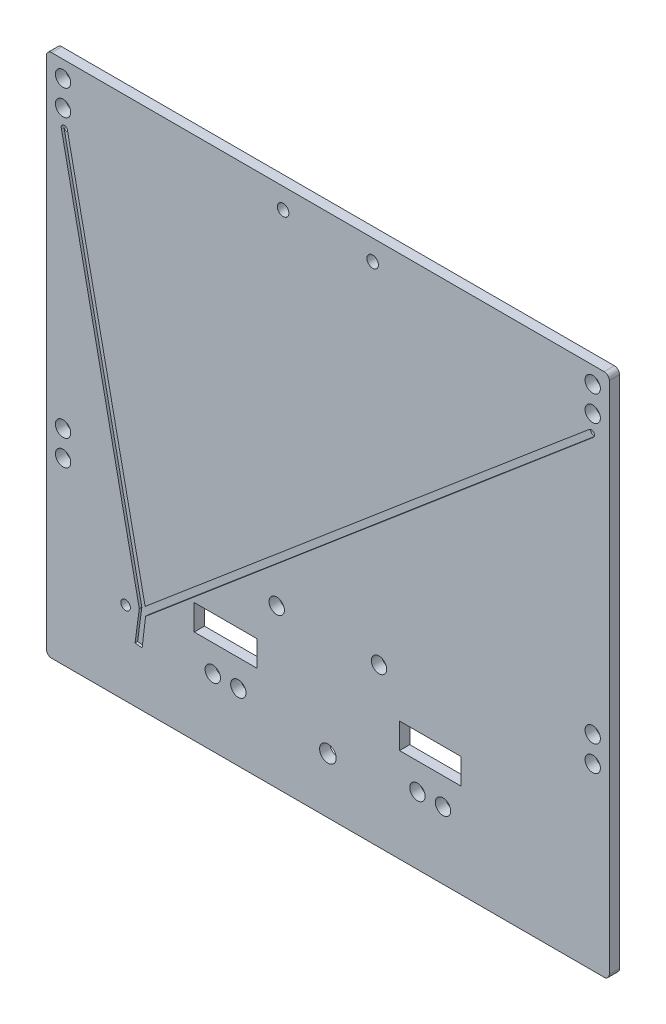
SolidWorks part; units mm, degrees
ref_plane "Front Plane" through (0, 0, 0) normal (0, 0, 1) x (1, 0, 0)
ref_plane "Top Plane" through (0, 0, 0) normal (0, 1, 0) x (1, 0, 0)
ref_plane "Right Plane" through (0, 0, 0) normal (1, 0, 0) x (0, 0, -1)
sketch "Sketch1" plane through (0, 0, 384.6201) normal (0, 0, -1) x (-1, 0, 0)
  line L5 (7.2108, -530.2989) -> (55.2108, -530.2989)
  line L6 (7.2108, -530.2989) -> (7.2108, -510.2989)
  line L7 (7.2108, -510.2989) -> (55.2108, -510.2989)
  line L8 (-108.7892, -197.7989) -> (-108.7892, -599.7989)
  line L9 (-104.7892, -603.7989) -> (327.2108, -603.7989)
  line L10 (331.2108, -599.7989) -> (331.2108, -197.7989)
  line L11 (327.2108, -193.7989) -> (-104.7892, -193.7989)
  line L12 (-108.7892, -197.7989) -> (-108.7892, -599.7989)
  line L13 (-104.7892, -603.7989) -> (327.2108, -603.7989)
  line L14 (331.2108, -599.7989) -> (331.2108, -197.7989)
  line L15 (327.2108, -193.7989) -> (-104.7892, -193.7989)
  line L16 (55.2108, -530.2989) -> (55.2108, -510.2989)
  line L17 (7.2108, -530.2989) -> (55.2108, -510.2989) construction
  line L18 (7.2108, -510.2989) -> (55.2108, -530.2989) construction
  line L19 (166.7108, -530.2989) -> (215.7108, -530.2989)
  line L20 (166.7108, -530.2989) -> (166.7108, -510.2989)
  line L21 (166.7108, -510.2989) -> (215.7108, -510.2989)
  line L22 (215.7108, -530.2989) -> (215.7108, -510.2989)
  line L23 (166.7108, -530.2989) -> (215.7108, -510.2989) construction
  line L24 (166.7108, -510.2989) -> (215.7108, -530.2989) construction
  circle A4 centre (-95.7892, -206.7989) radius 6
  circle A5 centre (-95.7892, -226.7989) radius 6
  circle A6 centre (146.2108, -209.7989) radius 4.5
  circle A7 centre (76.2108, -209.7989) radius 4.5
  arc A8 (-108.7892, -599.7989) -> (-104.7892, -603.7989) centre (-104.7892, -599.7989) ccw
  arc A9 (327.2108, -603.7989) -> (331.2108, -599.7989) centre (327.2108, -599.7989) ccw
  arc A10 (331.2108, -197.7989) -> (327.2108, -193.7989) centre (327.2108, -197.7989) ccw
  arc A11 (-104.7892, -193.7989) -> (-108.7892, -197.7989) centre (-104.7892, -197.7989) ccw
  arc A12 (-108.7892, -599.7989) -> (-104.7892, -603.7989) centre (-104.7892, -599.7989) ccw
  arc A13 (327.2108, -603.7989) -> (331.2108, -599.7989) centre (327.2108, -599.7989) ccw
  arc A14 (331.2108, -197.7989) -> (327.2108, -193.7989) centre (327.2108, -197.7989) ccw
  arc A15 (-104.7892, -193.7989) -> (-108.7892, -197.7989) centre (-104.7892, -197.7989) ccw
  circle A16 centre (318.2108, -206.7989) radius 6
  circle A17 centre (318.2108, -226.7989) radius 6
  circle A18 centre (-95.7892, -443.7989) radius 6
  circle A19 centre (-95.7892, -463.7989) radius 6
  circle A20 centre (318.2108, -443.7989) radius 6
  circle A21 centre (318.2108, -463.7989) radius 6
  circle A22 centre (71.2108, -480.2989) radius 6
  circle A23 centre (151.2108, -480.2989) radius 6
  circle A24 centre (21.2108, -551.2989) radius 6
  circle A25 centre (41.2108, -551.2989) radius 6
  circle A26 centre (111.2108, -560.2989) radius 6.5
  circle A27 centre (181.2108, -551.2989) radius 6
  circle A28 centre (269.3605, -538.8682) radius 3.735
  circle A29 centre (201.2108, -551.2989) radius 6
  point P66 (31.2108, -520.2989)
  point P71 (191.2108, -520.2989)
  dimension "D2" = 13
  dimension "D3" = 16
  dimension "D4" = 16
  dimension "D1" = 0
extrude "Boss-Extrude1" add sketch "Sketch1" along normal blind 8
sketch "Sketch2" plane through (0, 0, 384.6201) normal (0, 0, -1) x (-1, 0, 0)
  circle A0 centre (-94.6889, -240.6327) radius 2.5
  circle A1 centre (317.195, -240.6327) radius 2.5
  dimension "D1" = 5
extrude "Cut-Extrude1" cut sketch "Sketch2" along normal blind 10
sketch "Sketch3" plane through (0, 0, 384.6201) normal (0, 0, 1) x (1, 0, 0)
  line L0 (92.9374, -238.8488) -> (96.2783, -242.5625)
  line L1 (92.9374, -238.8488) -> (-254.0695, -532.153)
  line L2 (96.2783, -242.5625) -> (-253.7063, -538.6687)
  line L3 (-253.7063, -538.6687) -> (-256.4166, -561.4658)
  line L4 (-256.4166, -561.4658) -> (-261.937, -560.8094)
  line L5 (-261.937, -560.8094) -> (-258.6519, -536.0262)
  line L6 (-314.695, -240.6327) -> (-254.0695, -532.153)
  line L7 (-319.695, -240.6327) -> (-258.6519, -536.0262)
  line L8 (-314.695, -240.6327) -> (-319.695, -240.6327)
  circle A1 centre (94.6889, -240.6327) radius 2.5 construction
  circle A2 centre (-317.195, -240.6327) radius 2.5 construction
  dimension "D1" = 6
  dimension "D2" = 25
extrude "Cut-Extrude2" cut sketch "Sketch3" against normal blind 2
